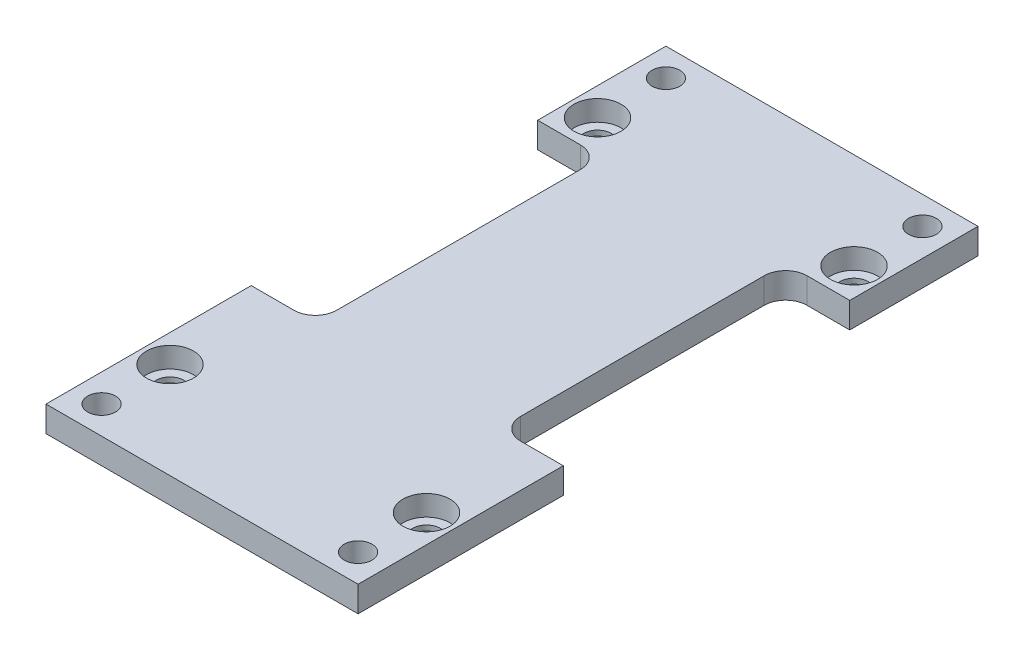
SolidWorks part; units mm, degrees
ref_plane "Front Plane" through (0, 0, 0) normal (0, 0, 1) x (1, 0, 0)
ref_plane "Top Plane" through (0, 0, 0) normal (0, 1, 0) x (1, 0, 0)
ref_plane "Right Plane" through (0, 0, 0) normal (1, 0, 0) x (0, 0, -1)
sketch "Sketch1" plane through (0, 0, 0) normal (0, 1, 0) x (1, 0, 0)
  line L0 (0, 72.5) -> (0, -72.5) construction
  line L1 (-36.5, -72.5) -> (36.5, -72.5)
  line L2 (-36.5, -72.5) -> (-36.5, 72.5) construction
  line L3 (-36.5, 72.5) -> (36.5, 72.5)
  line L4 (36.5, -72.5) -> (36.5, 72.5) construction
  line L5 (-36.5, -72.5) -> (36.5, 72.5) construction
  line L6 (-36.5, 72.5) -> (36.5, -72.5) construction
  line L7 (-36.5, 42.5) -> (-26.5, 42.5)
  line L8 (-21.5, 37.5) -> (-21.5, -19.5)
  line L9 (-26.5, -24.5) -> (-36.5, -24.5)
  line L10 (-36.5, -24.5) -> (-36.5, -72.5)
  line L11 (-36.5, 42.5) -> (-36.5, 72.5)
  line L12 (36.5, -24.5) -> (36.5, -72.5)
  line L13 (26.5, -24.5) -> (36.5, -24.5)
  line L14 (21.5, 37.5) -> (21.5, -19.5)
  line L15 (36.5, 42.5) -> (26.5, 42.5)
  line L16 (36.5, 42.5) -> (36.5, 72.5)
  arc A12 (26.5, -24.5) -> (21.5, -19.5) centre (26.5, -19.5) cw
  arc A13 (21.5, 37.5) -> (26.5, 42.5) centre (26.5, 37.5) cw
  arc A14 (-21.5, -19.5) -> (-26.5, -24.5) centre (-26.5, -19.5) cw
  arc A15 (-26.5, 42.5) -> (-21.5, 37.5) centre (-26.5, 37.5) cw
  point P0 (0, 0)
  point P40 (21.5, -24.5)
  point P43 (21.5, 42.5)
  point P46 (-21.5, -24.5)
  point P49 (-21.5, 42.5)
  dimension "D3" = 30
  dimension "D4" = 48
  dimension "D5" = 5
  dimension "D1" = 73
  dimension "D2" = 145
  dimension "D6" = 15
extrude "Boss-Extrude1" add sketch "Sketch1" along normal blind 6
sketch "Sketch2" plane through (0, 6, 0) normal (0, 1, 0) x (1, 0, 0)
  line L0 (0, 0) -> (50000, 0) construction
  line L1 (0, 0) -> (0, 50000) construction
  line L2 (36.5, 72.5) -> (-36.5, 72.5) construction
  line L3 (-36.5, 72.5) -> (-36.5, 42.5) construction
  line L4 (-30, 66) -> (-30, 50) construction
  circle A0 centre (-30, 66) radius 3.25
  circle A1 centre (-30, 50) radius 3.25
  circle A2 centre (30, 50) radius 3.25
  circle A3 centre (30, 66) radius 3.25
  circle A4 centre (30, -50) radius 3.25
  circle A5 centre (30, -66) radius 3.25
  circle A6 centre (-30, -50) radius 3.25
  circle A7 centre (-30, -66) radius 3.25
  dimension "D1" = 6.5
  dimension "D2" = 6.5
  dimension "D3" = 6.5
  dimension "D4" = 16
extrude "Cut-Extrude1" cut sketch "Sketch2" against normal through all
sketch "Sketch3" plane through (0, 6, 0) normal (0, 1, 0) x (1, 0, 0)
  line L0 (0, 0) -> (50000, 0) construction
  line L1 (0, 0) -> (0, 50000) construction
  circle A0 centre (-30, 50) radius 3.25 construction
  circle A1 centre (-30, 50) radius 3.25 construction
  circle A2 centre (-30, 50) radius 5.5
  circle A3 centre (30, 50) radius 5.5
  circle A4 centre (30, -50) radius 5.5
  circle A5 centre (-30, -50) radius 5.5
  dimension "D1" = 11
extrude "Cut-Extrude2" cut sketch "Sketch3" against normal blind 4.8
